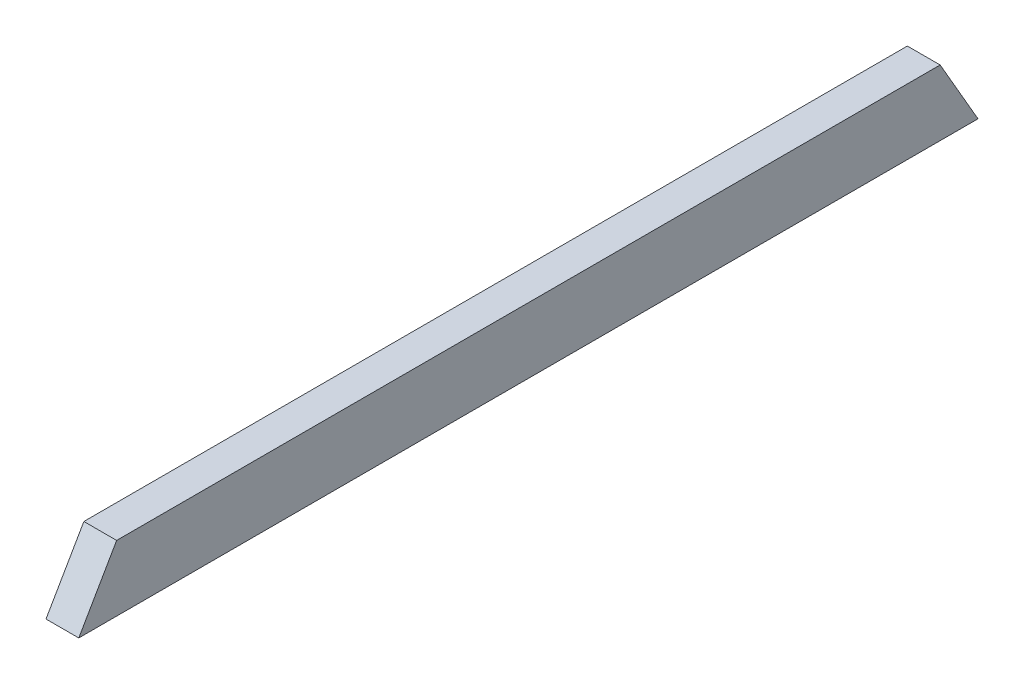
SolidWorks part; units mm, degrees
ref_plane "Front Plane" through (0, 0, 0) normal (0, 0, 1) x (1, 0, 0)
ref_plane "Top Plane" through (0, 0, 0) normal (0, 1, 0) x (1, 0, 0)
ref_plane "Right Plane" through (0, 0, 0) normal (1, 0, 0) x (0, 0, -1)
sketch "Sketch1" plane through (0, 0, 0) normal (0, 0, 1) x (1, 0, 0)
  line L1 (0, 0) -> (-44.45, 0)
  line L2 (0, 0) -> (0, 88.9)
  line L3 (0, 88.9) -> (-44.45, 88.9)
  line L4 (-44.45, 0) -> (-44.45, 88.9)
  dimension "D1" = 88.9
  dimension "D2" = 44.45
extrude "Boss-Extrude1" add sketch "Sketch1" along normal blind 1219.2
sketch "Sketch3" plane through (0, 0, 0) normal (1, 0, 0) x (0, 0, -1)
  line L0 (-1219.2, 0) -> (-1167.8736, 88.9)
  line L1 (-1219.2, 88.9) -> (0, 88.9) construction
  line L2 (-1167.8736, 88.9) -> (-1219.2, 88.9)
  line L3 (-1219.2, 88.9) -> (-1219.2, 0)
  line L4 (-51.3264, 88.9) -> (0, 88.9)
  line L5 (0, 88.9) -> (0, 0)
  line L6 (0, 0) -> (-51.3264, 88.9)
  dimension "D1" = 30
  dimension "D2" = 30
extrude "Cut-Extrude2" cut sketch "Sketch3" against normal blind 88.9
